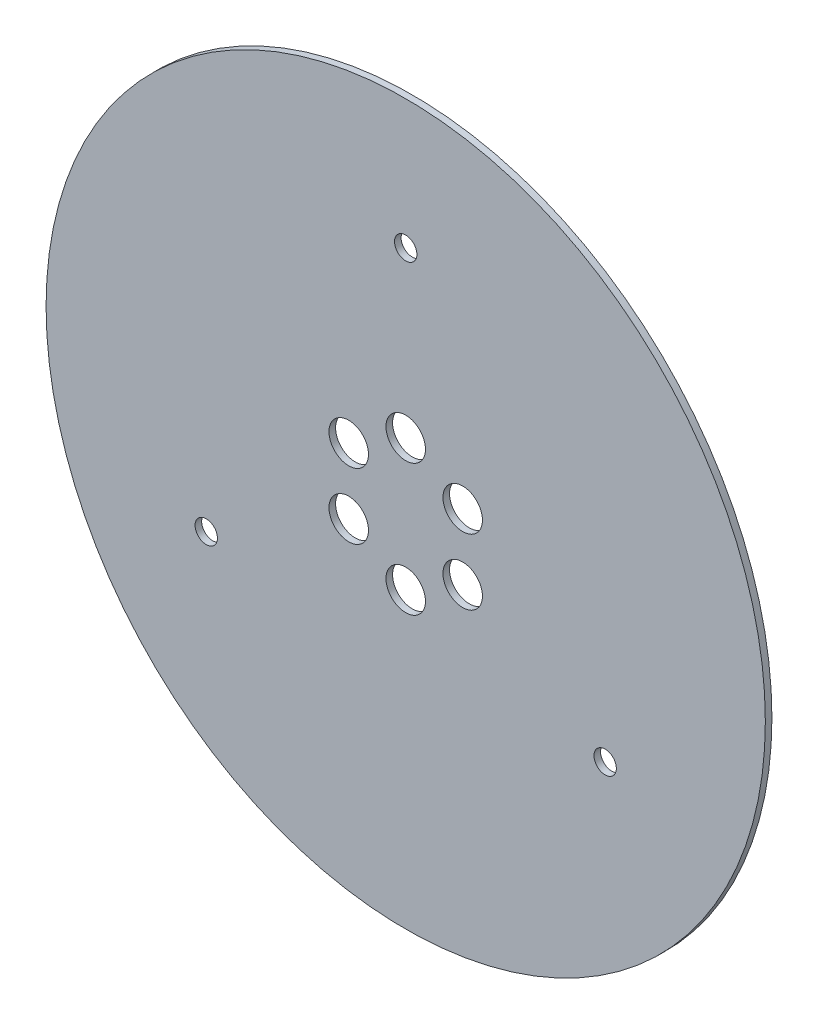
SolidWorks part; units mm, degrees
material "PETG"
ref_plane "Front Plane" through (0, 0, 0) normal (0, 0, 1) x (1, 0, 0)
ref_plane "Top Plane" through (0, 0, 0) normal (0, 1, 0) x (1, 0, 0)
ref_plane "Right Plane" through (0, 0, 0) normal (1, 0, 0) x (0, 0, -1)
sketch "Sketch1" plane through (0, 0, 0) normal (0, 0, 1) x (1, 0, 0)
  line L0 (0, 0) -> (0, 35) construction
  line L1 (0, 0) -> (0, 10) construction
  circle A0 centre (0, 0) radius 54.6563
  circle A1 centre (0, 35) radius 1.7
  circle A2 centre (30.3109, -17.5) radius 1.7
  circle A3 centre (-30.3109, -17.5) radius 1.7
  circle A4 centre (0, 10) radius 3
  circle A5 centre (8.6603, 5) radius 3
  circle A6 centre (8.6603, -5) radius 3
  circle A7 centre (0, -10) radius 3
  circle A8 centre (-8.6603, -5) radius 3
  circle A9 centre (-8.6603, 5) radius 3
  point P11 (0, 0)
  dimension "D1" = 109.3127
  dimension "D2" = 3.4
  dimension "D4" = 6
  dimension "D7" = 35
  dimension "D5" = 10
  dimension "D6" = 3
  dimension "D3" = 6
extrude "Boss-Extrude1" add sketch "Sketch1" along normal blind 1
equation "\"tol_dia_id_intfc\" = 0.0500mm ' For hole diameters - Interference fit"
equation "\"tol_dia_id_slip\"  = 0.0750mm ' For hole diameters - Slip fit"
equation "\"tol_dia_id_clear\" = 0.1000mm ' For hole diameters - Clearance fit"
equation "\"tol_dia_od_intfc\" = 0.0500mm ' For shaft diameters - Interference fit"
equation "\"tol_dia_od_slip\"  = 0.0750mm ' For shaft diameters - Slip fit"
equation "\"tol_dia_od_clear\" = 0.1000mm ' For shaft diameters - Clearance fit"
equation "\"tol_general_intfc\"= 0.0250mm ' For general parts (Horiz) - Interference fit"
equation "\"tol_general_slip\" = 0.0375mm ' For general parts (Horiz) - Slip fit"
equation "\"tol_general_clear\"= 0.0500mm ' For general parts (Horiz) - Clearance fit"
equation "\"tol_layer_intfc\"  = 0.0250mm ' For all parts (Vert) - Interference fit"
equation "\"tol_layer_slip\"   = 0.0375mm ' For all parts (Vert) - Slip fit"
equation "\"tol_layer_clear\"  = 0.0500mm ' For all parts (Vert) - Clearance fit"
equation "\"tol_corner_rad\"   = 0.100mm ' For corners that fit into other parts"
equation "\"pitch\"= 8mm"
equation "\"n\"= 39"
equation "\"pitch_dia\"= \"pitch\" * \"n\" / PI"
equation "\"belt_width\"= 22mm"
equation "\"D1@Sketch1\"=\"pitch_dia\"+10"
